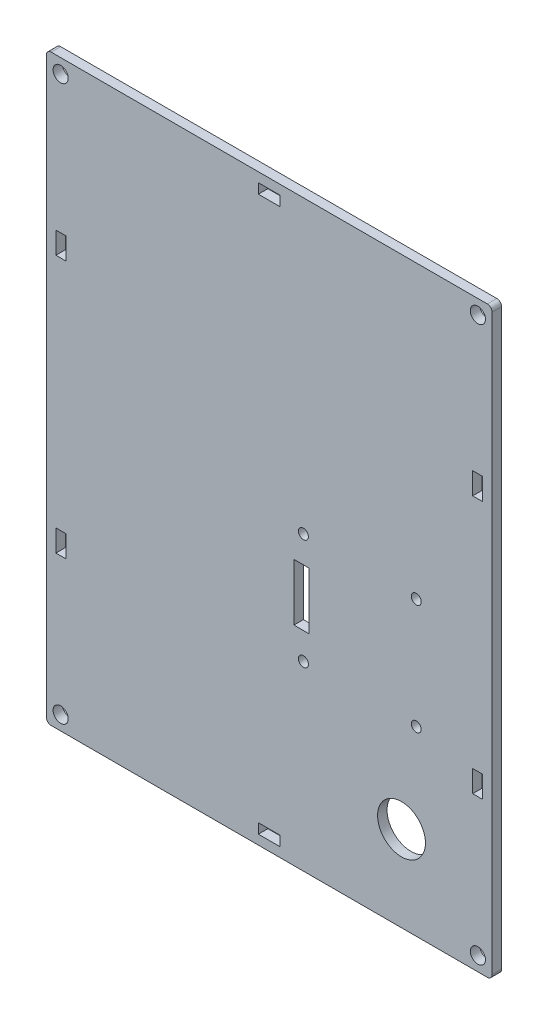
SolidWorks part; units mm, degrees
ref_plane "前基準面" through (0, 0, 0) normal (0, 0, 1) x (1, 0, 0)
ref_plane "上基準面" through (0, 0, 0) normal (0, 1, 0) x (1, 0, 0)
ref_plane "右基準面" through (0, 0, 0) normal (1, 0, 0) x (0, 0, -1)
sketch "Sketch1" plane through (0, 0, 0) normal (0, 0, 1) x (1, 0, 0)
  line L0 (0, 0) -> (-47, 0) construction
  line L1 (-47, 61.5) -> (47, 61.5)
  line L2 (-47, 61.5) -> (-47, -61.5)
  line L3 (-47, -61.5) -> (47, -61.5)
  line L4 (47, 61.5) -> (47, -61.5)
  line L5 (-47, 61.5) -> (47, -61.5) construction
  line L6 (-47, -61.5) -> (47, 61.5) construction
  line L7 (-47, 0) -> (47, 0) construction
  line L8 (0, 0) -> (0, -61.5) construction
  line L9 (0, -61.5) -> (0, 61.5) construction
  line L10 (-2.3, -57.4) -> (2.3, -57.4)
  line L11 (-2.3, 59.5) -> (2.3, 59.5)
  line L12 (-2.3, 59.5) -> (-2.3, 57.4)
  line L13 (-2.3, 57.4) -> (2.3, 57.4)
  line L14 (2.3, 59.5) -> (2.3, 57.4)
  line L15 (-2.3, 59.5) -> (2.3, 57.4) construction
  line L16 (-2.3, 57.4) -> (2.3, 59.5) construction
  line L17 (2.3, -59.5) -> (2.3, -57.4)
  line L18 (-2.3, -59.5) -> (2.3, -59.5)
  line L19 (-2.3, -59.5) -> (-2.3, -57.4)
  line L20 (-45, -24.9) -> (-42.9, -24.9)
  line L21 (-45, 29.5) -> (-42.9, 29.5)
  line L22 (-45, 29.5) -> (-45, 24.9)
  line L23 (-45, 24.9) -> (-42.9, 24.9)
  line L24 (-42.9, 29.5) -> (-42.9, 24.9)
  line L25 (-45, 29.5) -> (-42.9, 24.9) construction
  line L26 (-45, 24.9) -> (-42.9, 29.5) construction
  line L27 (-42.9, -29.5) -> (-42.9, -24.9)
  line L28 (-45, -29.5) -> (-42.9, -29.5)
  line L29 (-45, -29.5) -> (-45, -24.9)
  line L30 (45, -29.5) -> (45, -24.9)
  line L31 (45, -29.5) -> (42.9, -29.5)
  line L32 (42.9, -29.5) -> (42.9, -24.9)
  line L33 (45, -24.9) -> (42.9, -24.9)
  line L34 (45, 24.9) -> (42.9, 24.9)
  line L35 (42.9, 29.5) -> (42.9, 24.9)
  line L36 (45, 29.5) -> (42.9, 29.5)
  line L37 (45, 29.5) -> (45, 24.9)
  circle A0 centre (-44, 58.5) radius 1.6
  circle A1 centre (-44, -58.5) radius 1.6
  circle A2 centre (44, -58.5) radius 1.6
  circle A3 centre (44, 58.5) radius 1.6
  point P0 (0, 0)
  point P19 (0, 58.45)
  point P28 (-43.95, 27.2)
  dimension "D4" = 3.2
  dimension "D1" = 94
  dimension "D2" = 123
  dimension "D3" = 3
  dimension "D5" = 3
  dimension "D6" = 2
  dimension "D7" = 4.6
  dimension "D8" = 2.1
  dimension "D9" = 27.2
  dimension "D10" = 2
  dimension "D11" = 4.6
  dimension "D12" = 2.1
extrude "Boss-Extrude1" add sketch "Sketch1" along normal mid plane 2
fillet "Fillet1" radius 1 4 edges at (47, 61.5, 0) (47, -61.5, 0) (-47, -61.5, 0) (-47, 61.5, 0)
sketch "Sketch2" plane through (0, 0, 1) normal (0, 0, 1) x (1, 0, 0)
  line L0 (47, -60.5) -> (47, 60.5) construction
  line L1 (-46, -61.5) -> (46, -61.5) construction
  line L2 (19.1, -25.2) -> (19.1, 2.1) construction
  line L3 (5.2, 2.1) -> (33, 2.1)
  line L4 (5.2, 2.1) -> (5.2, -25.2)
  line L5 (5.2, -25.2) -> (33, -25.2)
  line L6 (33, 2.1) -> (33, -25.2)
  line L7 (5.2, 2.1) -> (33, -25.2) construction
  line L8 (5.2, -25.2) -> (33, 2.1) construction
  line L9 (5.2, -11.55) -> (33, -11.55) construction
  line L11 (5.2, -17.55) -> (8.4, -17.55)
  line L12 (5.2, -17.55) -> (5.2, -5.55)
  line L13 (5.2, -5.55) -> (8.4, -5.55)
  line L14 (8.4, -17.55) -> (8.4, -5.55)
  line L15 (5.2, -17.55) -> (8.4, -5.55) construction
  line L16 (5.2, -5.55) -> (8.4, -17.55) construction
  circle A0 centre (27.8901, -43.5) radius 5.05
  circle A1 centre (7.2, -23.2) radius 1.05
  circle A2 centre (31, -23.2) radius 1.05
  circle A3 centre (31, 0.1) radius 1.05
  circle A4 centre (7.2, 0.1) radius 1.05
  point P2 (19.1, -11.55)
  point P23 (6.8, -11.55)
  dimension "D1" = 10.1
  dimension "D7" = 2.1
  dimension "D2" = 19.1099
  dimension "D3" = 18
  dimension "D4" = 27.8
  dimension "D5" = 36.3
  dimension "27" = 27.3
  dimension "D6" = 14
  dimension "D8" = 2
  dimension "D9" = 2
  dimension "D10" = 12
  dimension "D11" = 3.2
  dimension "D12" = 3.2
extrude "Cut-Extrude1" cut sketch "Sketch2" against normal up to next contours L12 L11 L14 L13 | A1 | A2 | A4 | A3 | A0
